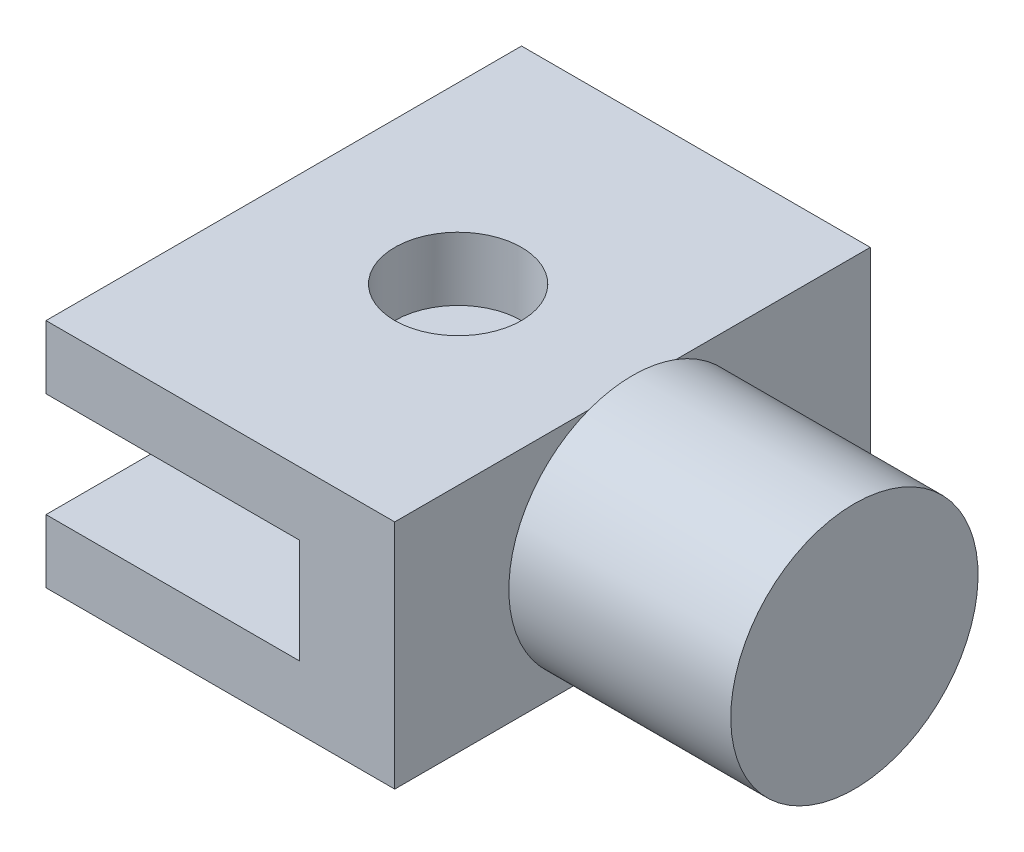
SolidWorks part; units mm, degrees
ref_plane "Front Plane" through (0, 0, 0) normal (0, 0, 1) x (1, 0, 0)
ref_plane "Top Plane" through (0, 0, 0) normal (0, 1, 0) x (1, 0, 0)
ref_plane "Right Plane" through (0, 0, 0) normal (1, 0, 0) x (0, 0, -1)
sketch "Sketch1" plane through (0, 0, 0) normal (0, 0, 1) x (1, 0, 0)
  line L0 (-8, 3.3) -> (-8, 5.3)
  line L1 (-8, 5.3) -> (3, 5.3)
  line L2 (3, 5.3) -> (3, -2)
  line L3 (3, -2) -> (-8, -2)
  line L4 (-8, -2) -> (-8, 0)
  line L5 (-8, 0) -> (0, 0)
  line L6 (0, 0) -> (0, 3.3)
  line L7 (0, 3.3) -> (-8, 3.3)
  dimension "D1" = 2
  dimension "D2" = 7.3
  dimension "D3" = 3.3
  dimension "D4" = 2
  dimension "D5" = 3
  dimension "D7" = 8
extrude "Boss-Extrude1" add sketch "Sketch1" along normal blind 15
sketch "Sketch4" plane through (3, 0, 0) normal (1, 0, 0) x (0, 0, -1)
  line L0 (-15, -2) -> (0, -2) construction
  line L1 (-15, -2) -> (-15, 5.3) construction
  circle A0 centre (-7.5, 1.65) radius 3.9
  point P7 (-7.5, -2)
  point P10 (-15, 1.65)
  dimension "D2" = 7.8
sketch "Sketch5" plane through (0, 5.3, 0) normal (0, 1, 0) x (1, 0, 0)
  line L4 (3, -15) -> (3, 0) construction
  line L5 (3, -15) -> (-8, -15) construction
  circle A0 centre (-2.5, -7.5) radius 2
  point P2 (0, 0)
  point P3 (-5, -11)
  point P4 (0, 0)
  point P5 (0, 0)
  point P8 (3, -7.5)
  point P11 (-2.5, -15)
extrude "Cut-Extrude1" cut sketch "Sketch5" against normal through all
extrude "Boss-Extrude2" add sketch "Sketch4" along normal blind 7
